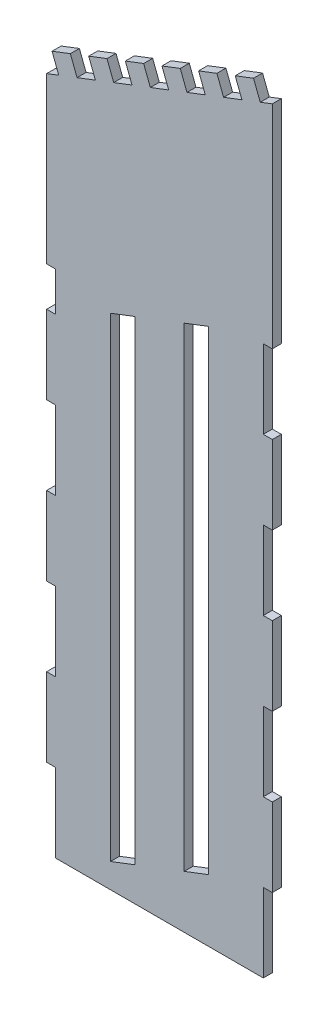
SolidWorks part; units mm, degrees
ref_plane "Front Plane" through (0, 0, 0) normal (0, 0, 1) x (1, 0, 0)
ref_plane "Top Plane" through (0, 0, 0) normal (0, 1, 0) x (1, 0, 0)
ref_plane "Right Plane" through (0, 0, 0) normal (1, 0, 0) x (0, 0, -1)
sketch "Sketch1" plane through (0, 0, 0) normal (0, 0, 1) x (1, 0, 0)
  line L0 (-36.5179, 109.22) -> (36.5179, 109.22) construction
  line L1 (-36.5179, 109.22) -> (36.5179, 137.2558)
  line L2 (-36.5179, 109.22) -> (-36.5179, -109.22)
  line L3 (-36.5179, -109.22) -> (36.5179, -109.22)
  line L4 (36.5179, 137.2558) -> (36.5179, -109.22)
  point P4 (0, 123.2379)
  point P7 (-36.5179, 0)
  dimension "D1" = 78.232
  dimension "D2" = 218.44
  dimension "D3" = 21
extrude "Boss-Extrude1" add sketch "Sketch1" along normal mid plane 2.921
sketch "Sketch2" plane through (0, 0, 1.4605) normal (0, 0, 1) x (1, 0, 0)
  line L0 (-33.5969, -109.22) -> (33.5969, -109.22)
  line L1 (-36.5179, 109.22) -> (36.5179, 109.22)
  line L2 (-36.5179, 109.22) -> (-36.5179, -109.22)
  line L3 (-36.5179, -109.22) -> (-33.5969, -109.22)
  line L4 (36.5179, 109.22) -> (36.5179, -109.22)
  line L5 (-36.5179, 109.22) -> (-33.5969, 109.22)
  line L6 (-36.5179, 109.22) -> (-36.5179, -109.22)
  line L7 (-36.5179, -109.22) -> (-33.5969, -109.22)
  line L8 (-33.5969, 109.22) -> (-33.5969, -109.22)
  line L9 (36.5179, -109.22) -> (33.5969, -109.22)
  line L10 (36.5179, -109.22) -> (36.5179, 109.22)
  line L11 (36.5179, 109.22) -> (33.5969, 109.22)
  line L12 (33.5969, -109.22) -> (33.5969, 109.22)
  line L13 (33.5969, -109.22) -> (36.5179, -109.22)
  line L14 (-36.5179, -83.82) -> (-33.5969, -83.82)
  line L15 (36.5179, -83.82) -> (33.5969, -83.82)
  line L16 (-36.5179, -58.42) -> (-33.5969, -58.42)
  line L17 (36.5179, -58.42) -> (33.5969, -58.42)
  line L18 (-36.5179, -33.02) -> (-33.5969, -33.02)
  line L19 (36.5179, -33.02) -> (33.5969, -33.02)
  line L20 (-36.5179, -7.62) -> (-33.5969, -7.62)
  line L21 (36.5179, -7.62) -> (33.5969, -7.62)
  line L22 (-36.5179, 17.78) -> (-33.5969, 17.78)
  line L23 (36.5179, 17.78) -> (33.5969, 17.78)
  line L24 (-36.5179, 43.18) -> (-33.5969, 43.18)
  line L25 (36.5179, 43.18) -> (33.5969, 43.18)
  line L26 (-36.5179, -109.22) -> (-36.5179, -83.82) construction
  line L27 (-36.5179, 55.88) -> (36.5179, 55.88)
  line L28 (-36.5179, 68.58) -> (-33.5969, 68.58)
  line L29 (0, 123.2379) -> (0, -109.22) construction
  line L31 (36.5179, 137.2558) -> (-36.5179, 109.22) construction
  line L32 (36.5179, 68.58) -> (33.5969, 68.58)
  point P40 (-35.0574, 43.18)
  point P47 (1.5069, -111.6675)
  point P48 (0, -109.22)
  line M28 (-36.5179, -109.22) -> (36.5179, -109.22)
  line M29 (36.5179, -109.22) -> (36.5179, 137.2558)
  dimension "D1" = 2.921
  dimension "D2" = 2.921
  dimension "D4" = 25.4
  dimension "D5" = 2.921
  dimension "D6" = 12.7
  dimension "D7" = 12.7
  dimension "D3" = 7
extrude "Cut-Extrude1" cut sketch "Sketch2" against normal blind 2.921 contours L14 L6 L8 M28 | L18 L6 L16 L8 | L22 L6 L20 L8 | L27 L6 L24 L8 | L27 L12 L25 M29 | L23 L12 L21 M29 | L15 L12 M29 M28 | L19 L12 L17 M29 | L10 L32 L12 L27
sketch "Sketch3" plane through (-41.2311, 107.4108, 0) normal (-0.3584, 0.9336, 0) x (0.9336, 0.3584, 0)
  line L0 (83.2805, 1.4605) -> (5.0485, 1.4605) construction
  line L1 (79.0895, 1.4605) -> (72.7395, 1.4605)
  line L2 (79.0895, 1.4605) -> (79.0895, -1.4605)
  line L3 (79.0895, -1.4605) -> (72.7395, -1.4605)
  line L4 (72.7395, 1.4605) -> (72.7395, -1.4605)
  line L5 (83.2805, -1.4605) -> (5.0485, -1.4605) construction
  line L6 (83.2805, -1.4605) -> (83.2805, 1.4605) construction
  line L7 (66.3895, 1.4605) -> (66.3895, -1.4605)
  line L8 (66.3895, 1.4605) -> (60.0395, 1.4605)
  line L9 (60.0395, 1.4605) -> (60.0395, -1.4605)
  line L10 (66.3895, -1.4605) -> (60.0395, -1.4605)
  line L11 (53.6895, 1.4605) -> (53.6895, -1.4605)
  line L12 (53.6895, 1.4605) -> (47.3395, 1.4605)
  line L13 (47.3395, 1.4605) -> (47.3395, -1.4605)
  line L14 (53.6895, -1.4605) -> (47.3395, -1.4605)
  line L15 (40.9895, 1.4605) -> (40.9895, -1.4605)
  line L16 (40.9895, 1.4605) -> (34.6395, 1.4605)
  line L17 (34.6395, 1.4605) -> (34.6395, -1.4605)
  line L18 (40.9895, -1.4605) -> (34.6395, -1.4605)
  line L19 (28.2895, 1.4605) -> (28.2895, -1.4605)
  line L20 (28.2895, 1.4605) -> (21.9395, 1.4605)
  line L21 (21.9395, 1.4605) -> (21.9395, -1.4605)
  line L22 (28.2895, -1.4605) -> (21.9395, -1.4605)
  line L23 (15.5895, 1.4605) -> (15.5895, -1.4605)
  line L24 (15.5895, 1.4605) -> (9.2395, 1.4605)
  line L25 (9.2395, 1.4605) -> (9.2395, -1.4605)
  line L26 (15.5895, -1.4605) -> (9.2395, -1.4605)
  line L27 (79.0895, 1.4605) -> (66.3895, 1.4605) construction
  point P10 (72.7395, 0)
  dimension "D1" = 4.191
  dimension "D2" = 6.35
  dimension "D4" = 12.7
  dimension "D3" = 6
extrude "Boss-Extrude2" add sketch "Sketch3" along normal blind 6.0452
sketch "Sketch5" plane through (0, 0, 1.4605) normal (0, 0, 1) x (1, 0, 0)
  line L0 (0, 123.2379) -> (0, -109.22) construction
  line L1 (-15.875, 52.3741) -> (-8.001, 55.3966)
  line L2 (-15.875, 52.3741) -> (-15.875, -101.2959)
  line L3 (-15.875, -101.2959) -> (-8.001, -98.2734)
  line L4 (-8.001, 55.3966) -> (-8.001, -98.2734)
  line L5 (8.001, 61.5392) -> (15.875, 64.5618)
  line L6 (8.001, 61.5392) -> (8.001, -92.1308)
  line L7 (8.001, -92.1308) -> (15.875, -89.1082)
  line L8 (15.875, 64.5618) -> (15.875, -89.1082)
  line L10 (-33.5969, -109.22) -> (33.5969, -109.22) construction
  line L12 (-8.001, 55.3966) -> (8.001, 61.5392) construction
  line L13 (-20.7488, 115.2732) -> (-26.6771, 112.9976) construction
  line L14 (-36.5179, -109.22) -> (36.5179, -81.1842) construction
  line L15 (36.5179, 68.58) -> (36.5179, 137.2558) construction
  line L16 (-33.5969, -109.22) -> (33.5969, -109.22) construction
  line L17 (36.5179, -83.82) -> (36.5179, -58.42) construction
  line L19 (0, -109.22) -> (-36.5179, -109.22) construction
  line L20 (-36.5179, 109.22) -> (-36.5179, -109.22) construction
  line L21 (-33.5969, -83.82) -> (-33.5969, -109.22) construction
  line L22 (-32.6053, 110.7219) -> (-36.5179, 109.22) construction
  line L23 (2.9641, 124.3757) -> (-2.9641, 122.1001) construction
  point P16 (0, 58.4679)
  point P26 (-33.5969, -108.0987)
  dimension "D1" = 31.75
  dimension "D2" = 21
  dimension "D3" = 153.67
  dimension "D4" = 7.874
extrude "Cut-Extrude2" cut sketch "Sketch5" against normal through all
